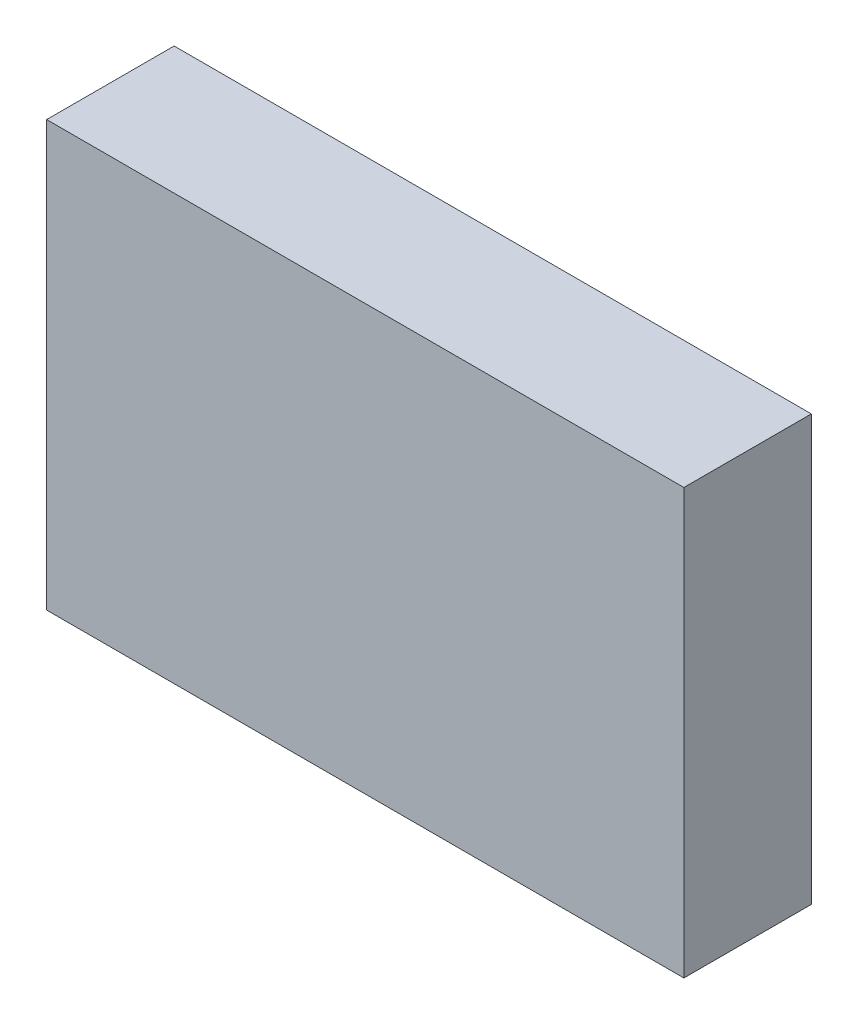
SolidWorks part; units mm, degrees
ref_plane "前视基准面" through (0, 0, 0) normal (0, 0, 1) x (1, 0, 0)
ref_plane "上视基准面" through (0, 0, 0) normal (0, 1, 0) x (1, 0, 0)
ref_plane "右视基准面" through (0, 0, 0) normal (1, 0, 0) x (0, 0, -1)
sketch "草图1" plane through (0, 0, 0) normal (0, 0, 1) x (1, 0, 0)
  line L1 (-75, -50) -> (75, -50)
  line L2 (-75, -50) -> (-75, 50)
  line L3 (-75, 50) -> (75, 50)
  line L4 (75, -50) -> (75, 50)
  line L5 (-75, -50) -> (75, 50) construction
  line L6 (-75, 50) -> (75, -50) construction
  point P0 (0, 0)
  dimension "D1" = 100
  dimension "D2" = 150
extrude "凸台-拉伸1" add sketch "草图1" along normal blind 30
